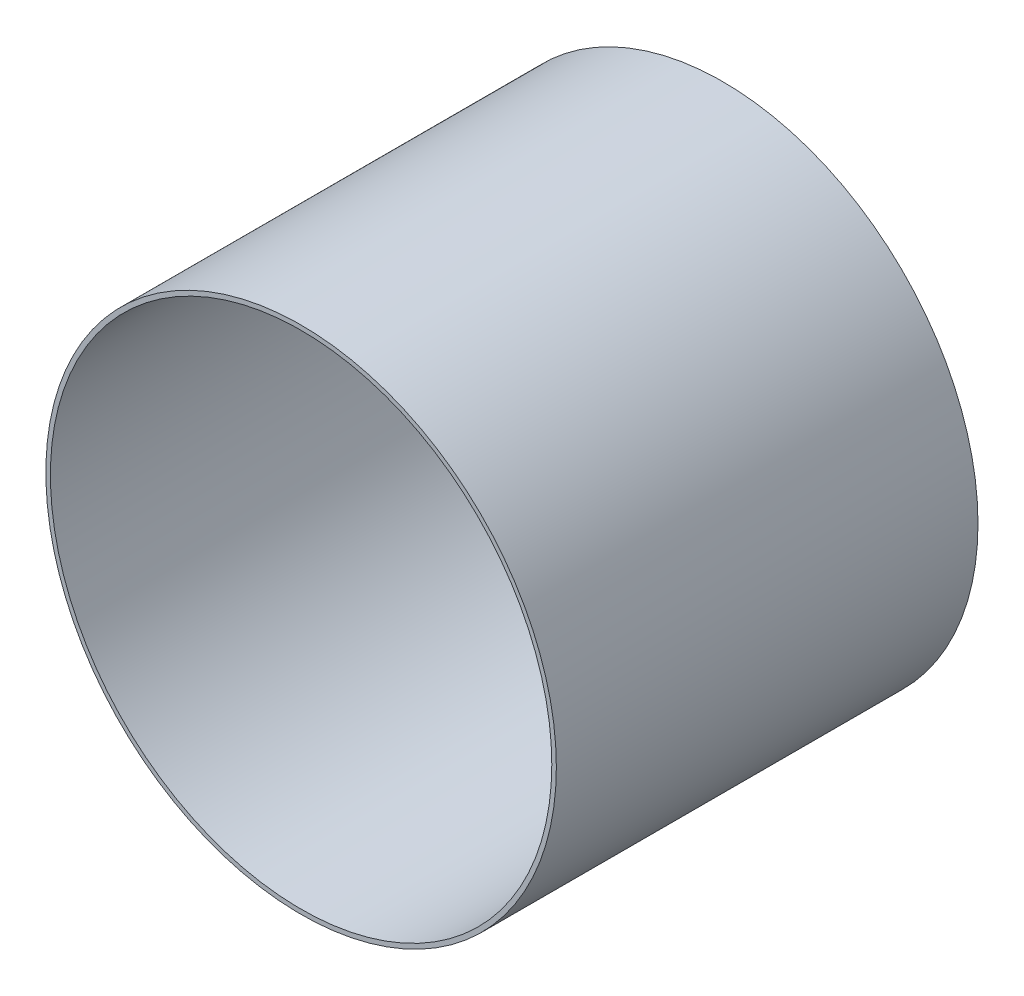
SolidWorks part; units mm, degrees
ref_plane "Front Plane" through (0, 0, 0) normal (0, 0, 1) x (1, 0, 0)
ref_plane "Top Plane" through (0, 0, 0) normal (0, 1, 0) x (1, 0, 0)
ref_plane "Right Plane" through (0, 0, 0) normal (1, 0, 0) x (0, 0, -1)
sketch "Sketch1" plane through (0, 0, 0) normal (0, 0, 1) x (1, 0, 0)
  circle A0 centre (0, 0) radius 71.12
  circle A1 centre (0, 0) radius 69.85
  dimension "D1" = 139.7
  dimension "D2" = 142.24
extrude "Extrude1" add sketch "Sketch1" along normal blind 117.475
